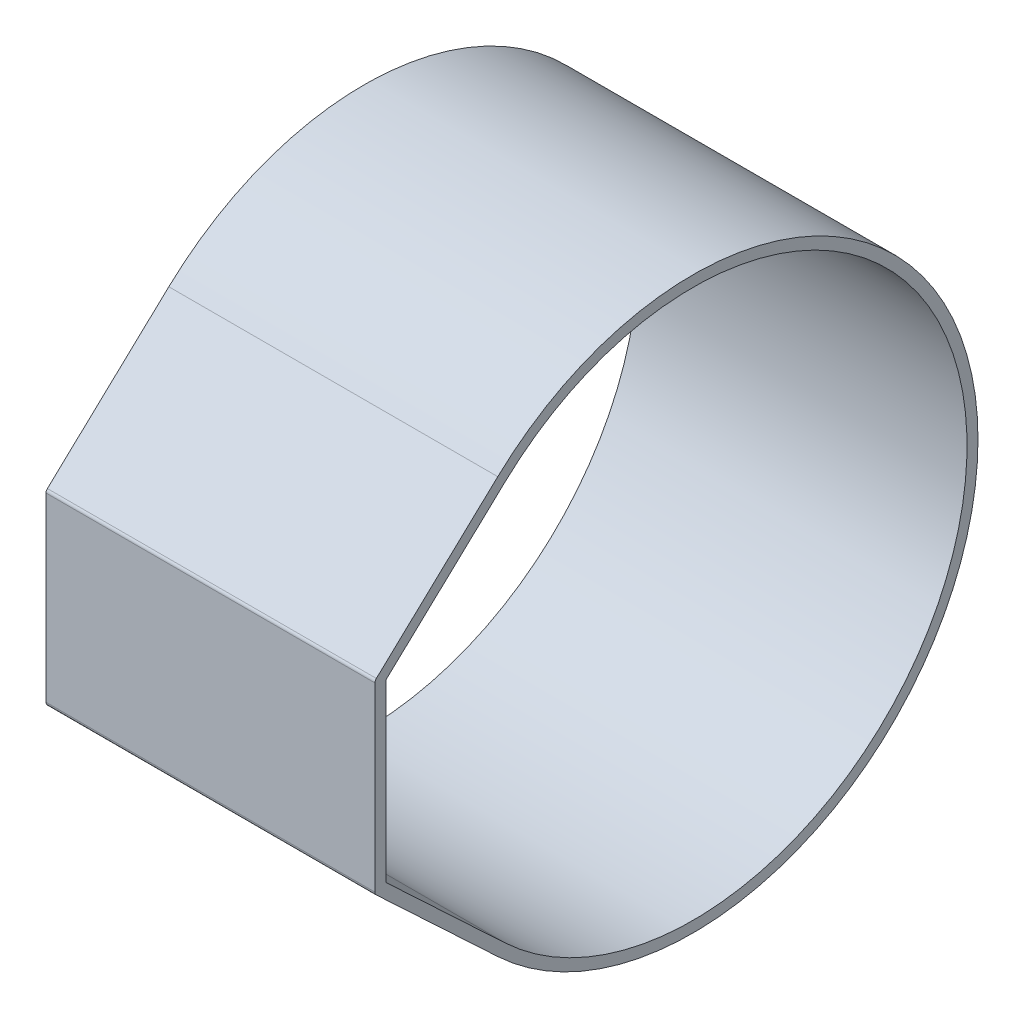
SolidWorks part; units mm, degrees
ref_plane "Front Plane" through (0, 0, 0) normal (0, 0, 1) x (1, 0, 0)
ref_plane "Top Plane" through (0, 0, 0) normal (0, 1, 0) x (1, 0, 0)
ref_plane "Right Plane" through (0, 0, 0) normal (1, 0, 0) x (0, 0, -1)
ref_plane "Plane1" through (-154.0071, 0, 0) normal (-1, 0, 0) x (0, -1, 0)
sketch "Sketch1" plane through (-154.0071, 0, 0) normal (-1, 0, 0) x (0, -1, 0)
  line L0 (-676.4436, -377.8003) -> (-671.332, -372.3577)
  line L1 (-671.332, -372.3577) -> (-663.332, -372.3577)
  line L2 (-663.332, -372.3577) -> (-658.2204, -377.8003)
  line L3 (-657.856, -377.458) -> (-663.0564, -371.9208)
  line L4 (-663.2022, -371.8577) -> (-671.4618, -371.8577)
  line L5 (-671.6076, -371.9208) -> (-676.808, -377.458)
  arc A0 (-658.2204, -377.8003) -> (-676.4436, -377.8003) centre (-667.332, -386.3577) cw
  arc A1 (-676.808, -377.458) -> (-657.856, -377.458) centre (-667.332, -386.3577) ccw
  arc A2 (-663.0564, -371.9208) -> (-663.2022, -371.8577) centre (-663.2022, -372.0577) ccw
  arc A3 (-671.4618, -371.8577) -> (-671.6076, -371.9208) centre (-671.4618, -372.0577) ccw
extrude "Boss-Extrude1" add sketch "Sketch1" against normal blind 15
